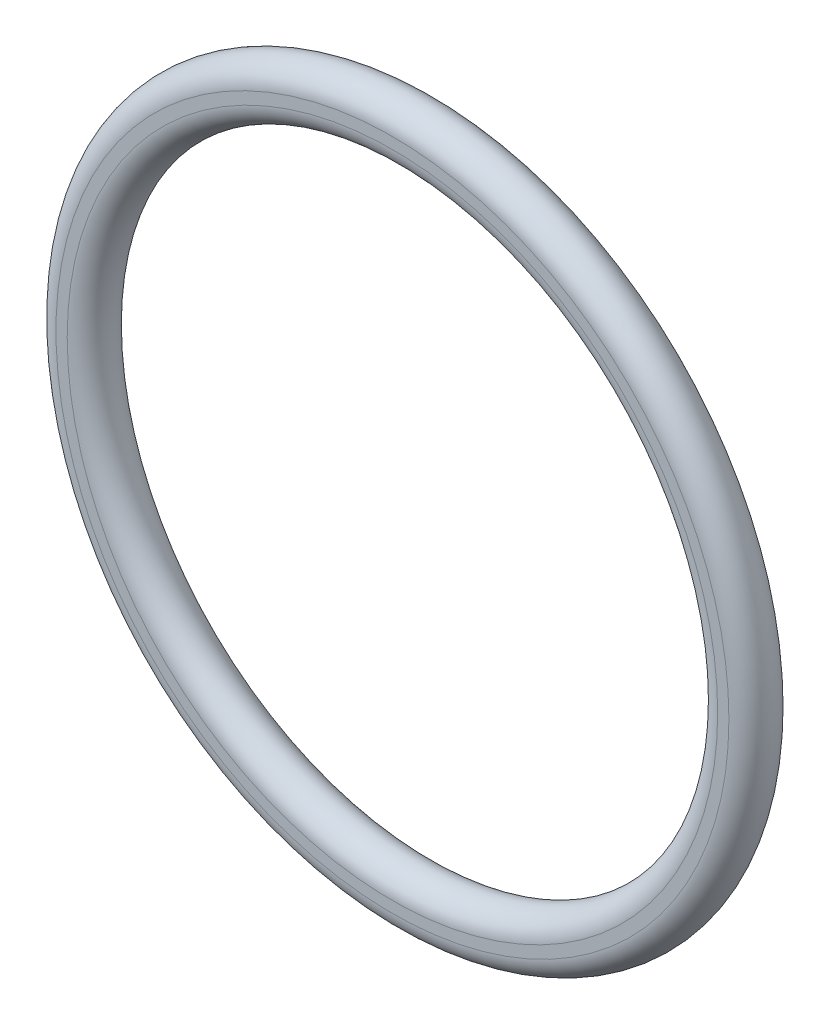
SolidWorks part; units mm, degrees
material "NEOPRENE"
ref_plane "Front Plane" through (0, 0, 0) normal (0, 0, 1) x (1, 0, 0)
ref_plane "Top Plane" through (0, 0, 0) normal (0, 1, 0) x (1, 0, 0)
ref_plane "Right Plane" through (0, 0, 0) normal (1, 0, 0) x (0, 0, -1)
sketch "Sketch1" plane through (0, 0, 0) normal (0, 1, 0) x (1, 0, 0)
  line L0 (23.0187, 0) -> (23.8125, 0) construction
  line L1 (23.0187, 1.5875) -> (23.8125, 1.5875)
  line L2 (23.0187, -1.5875) -> (23.8125, -1.5875)
  line L3 (23.8125, 0) -> (25.4, 0) construction
  line L4 (0, 0) -> (0, 17.7098) construction
  arc A0 (23.0187, 1.5875) -> (23.0187, -1.5875) centre (23.0187, 0) ccw
  arc A1 (23.8125, -1.5875) -> (23.8125, 1.5875) centre (23.8125, 0) ccw
  point P3 (23.4156, 0)
  dimension "D1" = 25.4
  dimension "D2" = 3.175
  dimension "D3" = 0.7937
revolve "Revolve1" add sketch "Sketch1" angle 360 about L4
